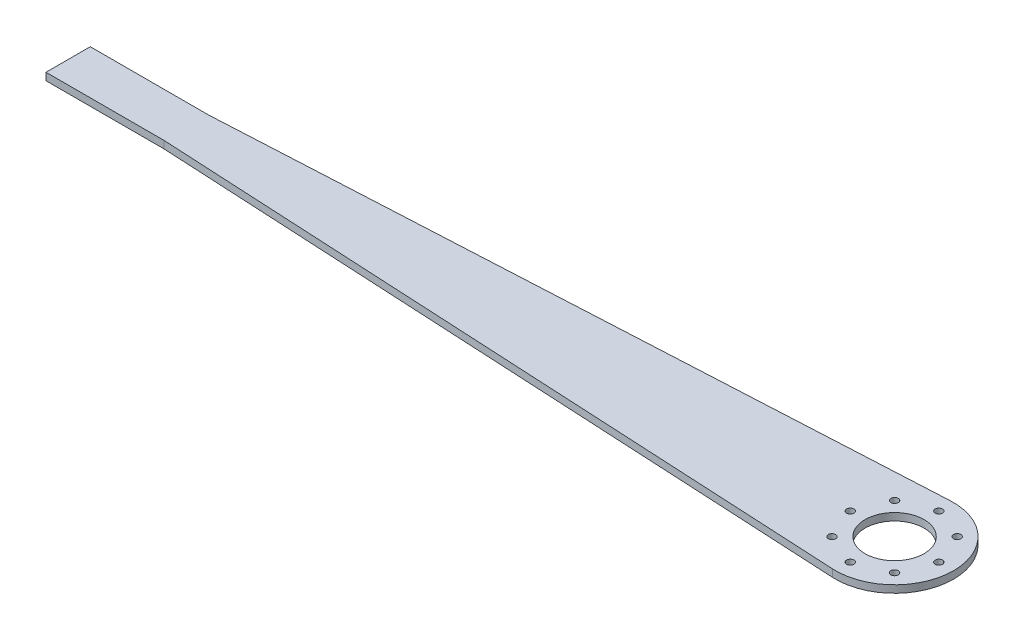
SolidWorks part; units mm, degrees
material "6061-T6 (SS)"
ref_plane "Front" through (0, 0, 0) normal (0, 0, 1) x (1, 0, 0)
ref_plane "Top" through (0, 0, 0) normal (0, 1, 0) x (1, 0, 0)
ref_plane "Right" through (0, 0, 0) normal (1, 0, 0) x (0, 0, -1)
sketch "Sketch5" plane through (0, 0, 0) normal (0, 1, 0) x (1, 0, 0)
  line L0 (-947.5926, 61.7606) -> (-1554.5446, 30.0796)
  line L1 (-1554.5446, 30.0796) -> (-1656.1446, 30.0796)
  line L2 (-1656.1446, 30.0796) -> (-1656.1446, -8.0204)
  line L3 (-1656.1446, -8.0204) -> (-1554.5446, -8.0204)
  line L4 (-1554.5446, -8.0204) -> (-947.5926, -39.7013)
  arc A0 (-947.5926, 61.7606) -> (-947.5926, -39.7013) centre (-944.9446, 11.0296) cw
  point P7 (-1605.3446, 30.0796)
  dimension "D1" = 19.05
  dimension "D2" = 19.05
  dimension "D5" = 50.8
  dimension "D6" = 711.2
  dimension "D3" = 101.6
  dimension "D4" = 101.6
extrude "Boss-Extrude1" add sketch "Sketch5" along normal blind 6.35
sketch "Sketch6" plane through (0, 6.35, 0) normal (0, 1, 0) x (1, 0, 0)
  circle A0 centre (-944.9446, 11.0296) radius 25.4
  dimension "D1" = 50.8
extrude "Cut-Extrude1" cut sketch "Sketch6" against normal through all
hole_wizard "1/4 (0.25) Diameter Hole1" positions "Sketch7" profile "Sketch8" hole size "1/4" standard "ANSI Inch" end condition through all
sketch "Sketch7" plane through (0, 6.35, 0) normal (0, 1, 0) x (1, 0, 0)
  circle A0 centre (-944.9446, 11.0296) radius 25.4 construction
  point P0 (-944.9446, 49.1296)
  dimension "D1" = 0
  dimension "D2" = 38.1
sketch "Sketch8" plane through (-944.9446, 6.35, -49.1296) normal (1, 0, 0) x (0, 0, 1)
  line L0 (0, 0) -> (0, 6.35)
  line L1 (0, 6.35) -> (3.175, 6.35)
  line L2 (3.175, 6.35) -> (3.175, 0)
  line L5 (3.175, 0) -> (0, 0)
  line L11 (0, -6.35) -> (0, 107.95) construction
  dimension "Thru Hole Dia." = 6.35
  dimension "Thru Hole Depth" = 6.35
pattern_circular "CirPattern1" count 8 over 360 about axis through (-944.9446, 0, -11.0296) along (0, 1, 0) of "1/4 (0.25) Diameter Hole1"
